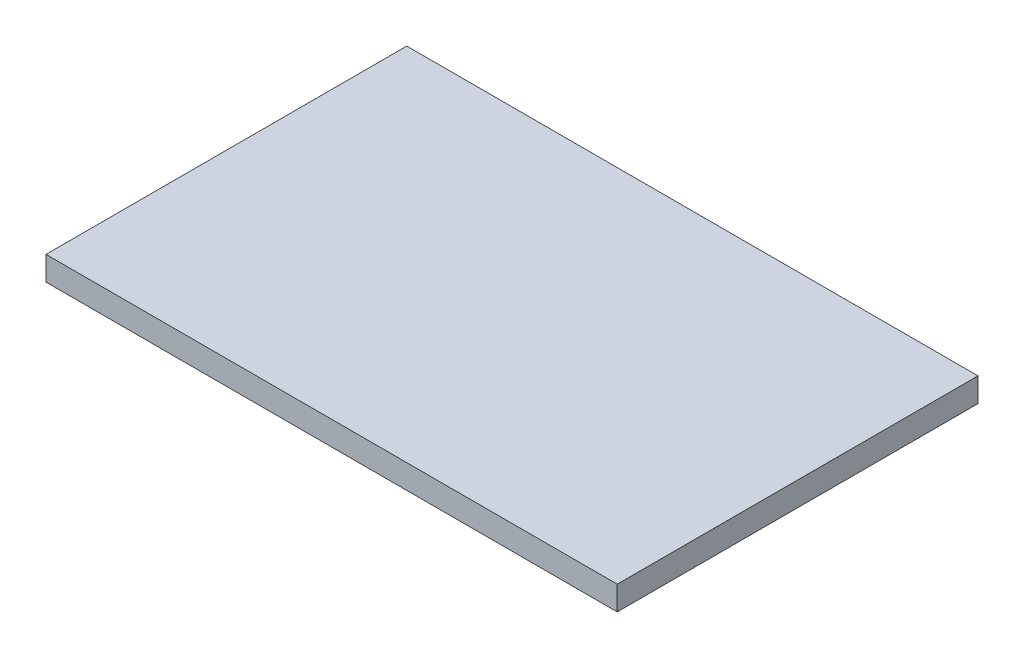
SolidWorks part; units mm, degrees
ref_plane "前视基准面" through (0, 0, 0) normal (0, 0, 1) x (1, 0, 0)
ref_plane "上视基准面" through (0, 0, 0) normal (0, 1, 0) x (1, 0, 0)
ref_plane "右视基准面" through (0, 0, 0) normal (1, 0, 0) x (0, 0, -1)
other "Configuration Table"
sketch "草图1" plane through (0, 0, 0) normal (0, 1, 0) x (1, 0, 0)
  line L1 (-47.5, -30) -> (47.5, -30)
  line L2 (-47.5, -30) -> (-47.5, 30)
  line L3 (-47.5, 30) -> (47.5, 30)
  line L4 (47.5, -30) -> (47.5, 30)
  line L5 (-47.5, -30) -> (47.5, 30) construction
  line L6 (-47.5, 30) -> (47.5, -30) construction
  point P0 (0, 0)
  dimension "D1" = 60
  dimension "D2" = 95
extrude "凸台-拉伸1" add sketch "草图1" along normal blind 4
